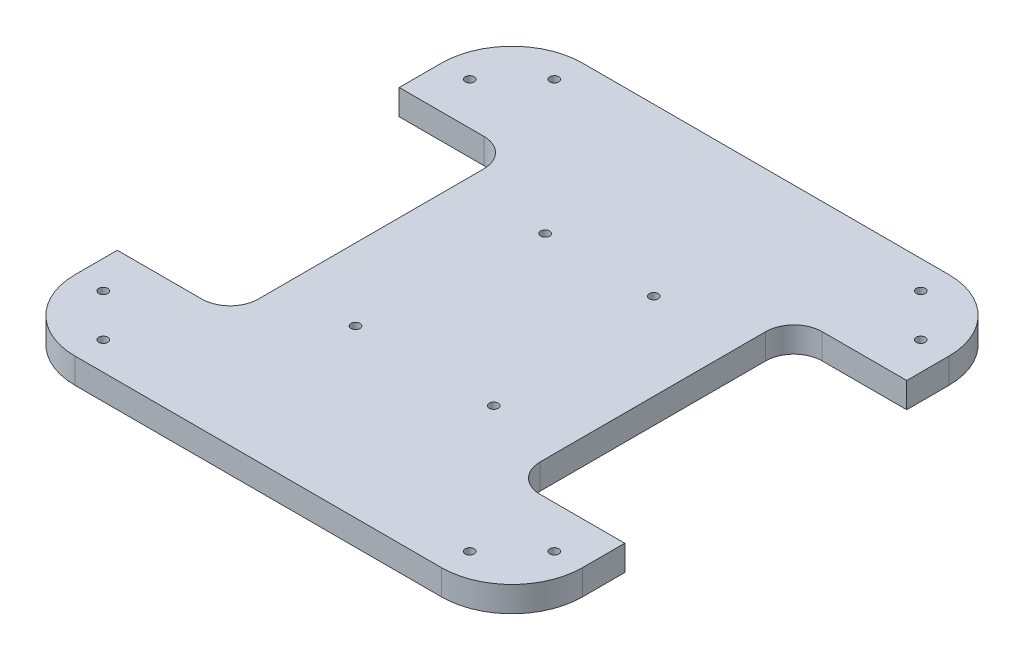
SolidWorks part; units mm, degrees
ref_plane "Front Plane" through (0, 0, 0) normal (0, 0, 1) x (1, 0, 0)
ref_plane "Top Plane" through (0, 0, 0) normal (0, 1, 0) x (1, 0, 0)
ref_plane "Right Plane" through (0, 0, 0) normal (1, 0, 0) x (0, 0, -1)
sketch "Sketch1" plane through (0, 0, 0) normal (0, 1, 0) x (1, 0, 0)
  line L1 (-65, -90) -> (65, -90)
  line L2 (-90, -65) -> (-90, 65)
  line L3 (-65, 90) -> (65, 90)
  line L4 (90, -65) -> (90, 65)
  arc A0 (-90, 65) -> (-65, 90) centre (-65, 65) cw
  arc A1 (65, 90) -> (90, 65) centre (65, 65) cw
  arc A2 (90, -65) -> (65, -90) centre (65, -65) cw
  arc A3 (-65, -90) -> (-90, -65) centre (-65, -65) cw
  point P4 (-90, 0)
  point P6 (0, 90)
  dimension "D3" = 25
  dimension "D1" = 180
  dimension "D2" = 180
extrude "Plate" add sketch "Sketch1" along normal blind 9
sketch "Sketch3" plane through (0, 9, 0) normal (0, 1, 0) x (1, 0, 0)
  line L0 (-65, 90) -> (-65, -90) construction
  line L1 (65, 90) -> (65, -90) construction
  line L2 (-90, 65) -> (90, 65) construction
  line L3 (-90, -65) -> (90, -65) construction
  circle A0 centre (-65, 80) radius 1.6
  circle A1 centre (-80, 65) radius 1.6
  circle A2 centre (80, 65) radius 1.6
  circle A3 centre (80, -65) radius 1.6
  circle A4 centre (65, 80) radius 1.6
  circle A5 centre (65, -80) radius 1.6
  circle A6 centre (-65, -80) radius 1.6
  circle A7 centre (-80, -65) radius 1.6
  dimension "D1" = 3.2
  dimension "D2" = 15
  dimension "D3" = 15
  dimension "D4" = 15
  dimension "D5" = 15
  dimension "D6" = 15
  dimension "D7" = 15
  dimension "D8" = 15
  dimension "D9" = 15
extrude "Hex Holes" cut sketch "Sketch3" against normal through all
sketch "Sketch4" plane through (0, 9, 0) normal (0, 1, 0) x (1, 0, 0)
  line L0 (-90, -65) -> (-90, 65) construction
  line L1 (-65, -90) -> (65, -90) construction
  circle A0 centre (-24.5, -31) radius 1.6
  circle A1 centre (24.5, -31) radius 1.6
  circle A2 centre (-19.25, 31) radius 1.6
  circle A3 centre (19.25, 31) radius 1.6
  dimension "D1" = 3.2
  dimension "D2" = 62
  dimension "D3" = 49
  dimension "D4" = 5.25
  dimension "D5" = 38.5
  dimension "D6" = 65.5
  dimension "D7" = 59
extrude "Arduino Holes" cut sketch "Sketch4" against normal through all
sketch "Sketch5" plane through (0, 9, 0) normal (0, 1, 0) x (1, 0, 0)
  line L0 (-90, -65) -> (-90, 65) construction
  line L1 (-90, -50) -> (-50, -50)
  line L2 (-90, -50) -> (-90, 50)
  line L3 (-90, 50) -> (-50, 50)
  line L4 (-50, -50) -> (-50, 50)
  line L5 (90, -65) -> (90, 65) construction
  line L6 (90, -50) -> (50, -50)
  line L7 (90, -50) -> (90, 50)
  line L8 (90, 50) -> (50, 50)
  line L9 (50, -50) -> (50, 50)
  line L10 (-90, 0) -> (90, 0) construction
  point P14 (-90, 0)
  point P15 (90, 0)
  dimension "D1" = 100
  dimension "D3" = 40
extrude "Cut-Extrude1" cut sketch "Sketch5" against normal through all
fillet "Fillet1" radius 10 4 edges at (50, 4.5, -50) (50, 4.5, 50) (-50, 4.5, -50) (-50, 4.5, 50)
